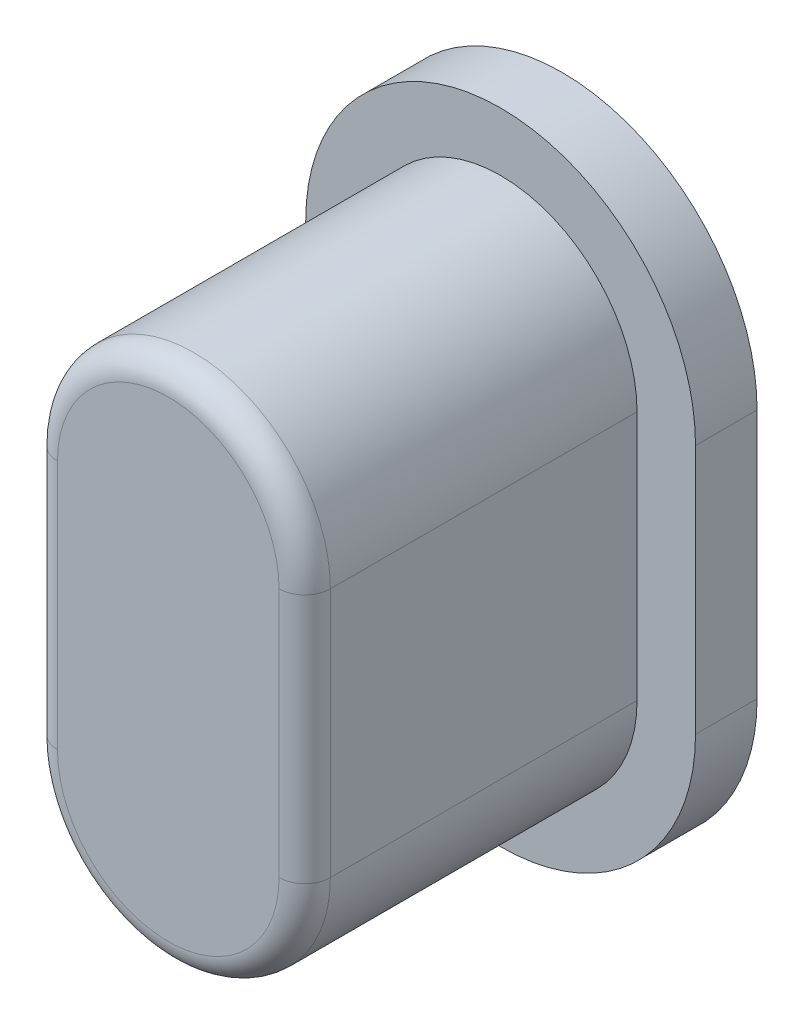
SolidWorks part; units mm, degrees
material "ABS"
ref_plane "Front Plane" through (0, 0, 0) normal (0, 0, 1) x (1, 0, 0)
ref_plane "Top Plane" through (0, 0, 0) normal (0, 1, 0) x (1, 0, 0)
ref_plane "Right Plane" through (0, 0, 0) normal (1, 0, 0) x (0, 0, -1)
sketch "Sketch1" plane through (0, 0, 0) normal (0, 0, 1) x (1, 0, 0)
  line L0 (0, -2.4377) -> (0, 2.4377) construction
  line L1 (-3.8, -2.4377) -> (-3.8, 2.4377)
  line L2 (3.8, -2.4377) -> (3.8, 2.4377)
  arc A0 (-3.8, -2.4377) -> (3.8, -2.4377) centre (0, -2.4377) ccw
  arc A1 (3.8, 2.4377) -> (-3.8, 2.4377) centre (0, 2.4377) ccw
  point P2 (0, 0)
  dimension "D1" = 7.6
  dimension "D2" = 4.8753
extrude "Boss-Extrude1" add sketch "Sketch1" along normal blind 1.2
sketch "Sketch2" plane through (0, 0, 1.2) normal (0, 0, 1) x (1, 0, 0)
  line L0 (2.66, -2.4377) -> (2.66, 2.4377)
  line L1 (-2.66, 2.4377) -> (-2.66, -2.4377)
  line L2 (3.8, -2.4377) -> (3.8, 2.4377)
  line L3 (-3.8, 2.4377) -> (-3.8, -2.4377)
  line L4 (3.8, -2.4377) -> (3.8, 2.4377) construction
  line L5 (-3.8, 2.4377) -> (-3.8, -2.4377) construction
  arc A0 (2.66, 2.4377) -> (-2.66, 2.4377) centre (0, 2.4377) ccw
  arc A1 (-2.66, -2.4377) -> (2.66, -2.4377) centre (0, -2.4377) ccw
  arc A2 (-3.8, -2.4377) -> (3.8, -2.4377) centre (0, -2.4377) ccw
  arc A3 (3.8, 2.4377) -> (-3.8, 2.4377) centre (0, 2.4377) ccw
  arc A4 (-3.8, -2.4377) -> (3.8, -2.4377) centre (0, -2.4377) ccw construction
  arc A5 (3.8, 2.4377) -> (-3.8, 2.4377) centre (0, 2.4377) ccw construction
  dimension "D1" = 0
  dimension "D2" = 1.14
extrude "Boss-Extrude2" add sketch "Sketch2" along normal blind 6.48
fillet "Fillet1" radius 0.5 4 edges at (-2.66, 0, 7.68) (0, 5.0977, 7.68) (2.66, 0, 7.68) (0, -5.0977, 7.68)
